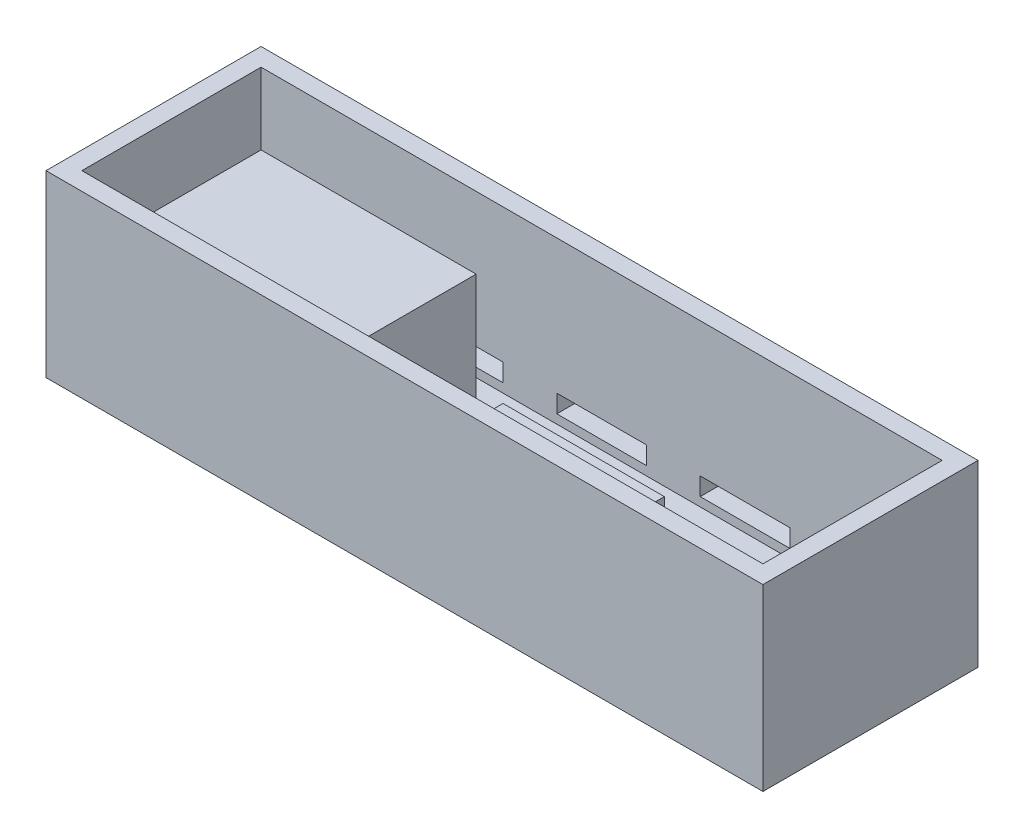
SolidWorks part; units mm, degrees
ref_plane "Plan de face" through (0, 0, 0) normal (0, 0, 1) x (1, 0, 0)
ref_plane "Plan de dessus" through (0, 0, 0) normal (0, 1, 0) x (1, 0, 0)
ref_plane "Plan de droite" through (0, 0, 0) normal (1, 0, 0) x (0, 0, -1)
sketch "Esquisse1" plane through (0, 0, 0) normal (0, 1, 0) x (1, 0, 0)
  line L1 (0, 0) -> (400, 0)
  line L2 (0, 0) -> (0, 120)
  line L3 (0, 120) -> (400, 120)
  line L4 (400, 0) -> (400, 120)
  dimension "D1" = 120
  dimension "D2" = 400
extrude "Boss.-Extru.1" add sketch "Esquisse1" along normal blind 100
sketch "Esquisse2" plane through (0, 100, 0) normal (0, 1, 0) x (1, 0, 0)
  line L9 (390, 10) -> (390, 110)
  line L10 (10, 10) -> (390, 10)
  line L11 (390, 110) -> (10, 110)
  line L12 (10, 110) -> (10, 10)
  line L13 (390, 10) -> (390, 110)
  line L14 (10, 10) -> (390, 10)
  line L15 (390, 110) -> (10, 110)
  line L16 (10, 110) -> (10, 10)
  dimension "D1" = 10
extrude "Enlèv. mat.-Extru.1" cut sketch "Esquisse2" against normal blind 90
sketch "Esquisse3" plane through (0, 10, 0) normal (0, 1, 0) x (1, 0, 0)
  line L0 (10, 10) -> (390, 10) construction
  line L1 (20, 100) -> (140, 100)
  line L2 (20, 100) -> (20, 20)
  line L3 (20, 20) -> (140, 20)
  line L4 (140, 100) -> (140, 20)
  point P4 (0, 0)
  dimension "D1" = 80
  dimension "D2" = 120
  dimension "D3" = 10
  dimension "D4" = 10
extrude "Boss.-Extru.2" add sketch "Esquisse3" along normal blind 60
sketch "Esquisse4" plane through (0, 10, 0) normal (0, 1, 0) x (1, 0, 0)
  line L1 (170, 85) -> (260, 85)
  line L2 (170, 85) -> (170, 35)
  line L3 (170, 35) -> (260, 35)
  line L4 (260, 85) -> (260, 35)
  line L5 (140, 20) -> (140, 100) construction
  point P4 (170, 60)
  point P5 (140, 60)
  point P9 (64.9076, -7.5033)
  dimension "D1" = 90
  dimension "D2" = 50
  dimension "D3" = 30
  dimension "D4" = 0
extrude "Boss.-Extru.3" add sketch "Esquisse4" along normal blind 20
sketch "Esquisse5" plane through (0, 10, 0) normal (0, 1, 0) x (1, 0, 0)
  line L0 (260, 35) -> (260, 85) construction
  line L1 (290, 70) -> (350, 70)
  line L2 (290, 70) -> (290, 50)
  line L3 (290, 50) -> (350, 50)
  line L4 (350, 70) -> (350, 50)
  point P4 (290, 60)
  point P7 (260, 60)
  dimension "D1" = 60
  dimension "D2" = 20
  dimension "D3" = 0
  dimension "D4" = 30
extrude "Boss.-Extru.4" add sketch "Esquisse5" along normal blind 20
sketch "Esquisse9" plane through (0, 0, -120) normal (0, 0, -1) x (-1, 0, 0)
  line L0 (-400, 0) -> (0, 0) construction
  line L1 (-385, 15) -> (-335, 15)
  line L2 (-385, 15) -> (-385, 25)
  line L3 (-385, 25) -> (-335, 25)
  line L4 (-335, 15) -> (-335, 25)
  line L5 (-400, 100) -> (-400, 0) construction
  dimension "D1" = 50
  dimension "D2" = 10
  dimension "D3" = 15
  dimension "D4" = 15
extrude "Enlèv. mat.-Extru.3" cut sketch "Esquisse9" against normal blind 10
pattern_linear "Répétition linéaire1" count 5 spacing 80 along (-1, 0, 0) of "Enlèv. mat.-Extru.3"
